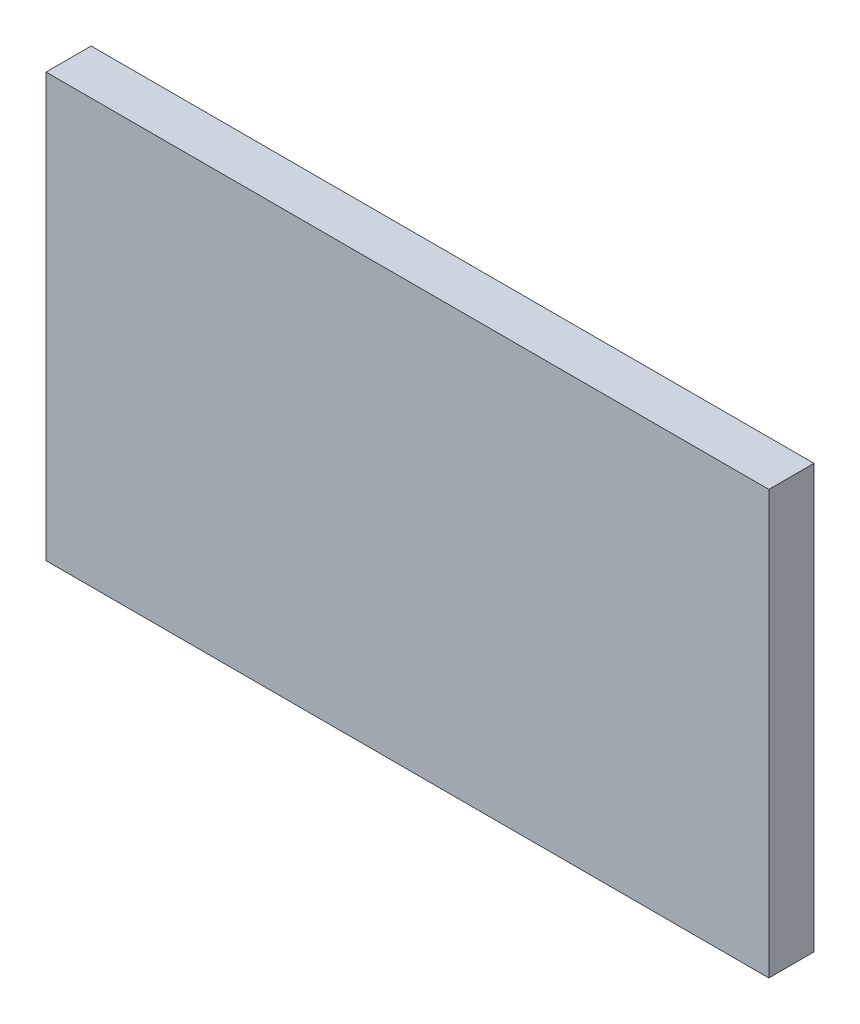
SolidWorks part; units mm, degrees
ref_plane "Front Plane" through (0, 0, 0) normal (0, 0, 1) x (1, 0, 0)
ref_plane "Top Plane" through (0, 0, 0) normal (0, 1, 0) x (1, 0, 0)
ref_plane "Right Plane" through (0, 0, 0) normal (1, 0, 0) x (0, 0, -1)
sketch "Sketch1" plane through (0, 0, 0) normal (0, 0, 1) x (1, 0, 0)
  line L1 (0, 0) -> (304.3664, 0)
  line L2 (0, 0) -> (0, 178.1726)
  line L3 (0, 178.1726) -> (304.3664, 178.1726)
  line L4 (304.3664, 0) -> (304.3664, 178.1726)
extrude "Boss-Extrude1" add sketch "Sketch1" along normal blind 19
